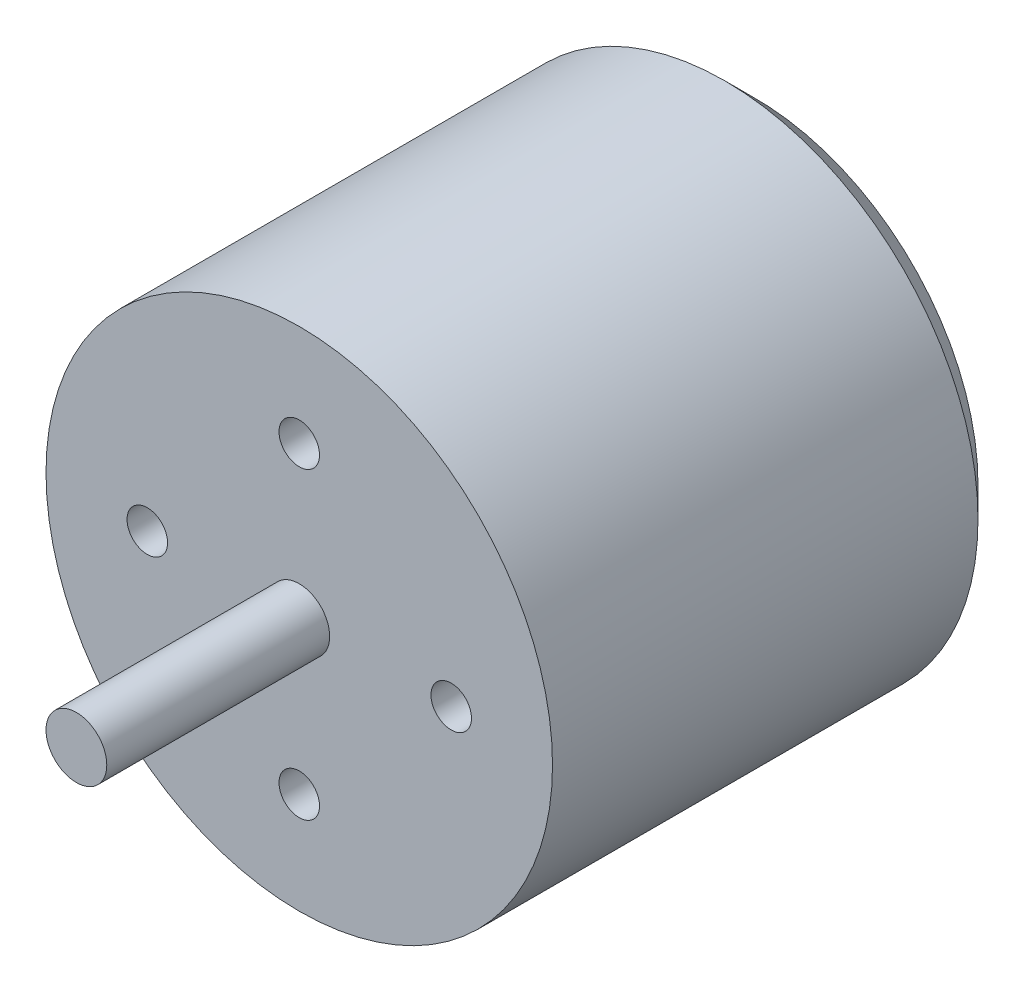
SolidWorks part; units mm, degrees
ref_plane "Front Plane" through (0, 0, 0) normal (0, 0, 1) x (1, 0, 0)
ref_plane "Top Plane" through (0, 0, 0) normal (0, 1, 0) x (1, 0, 0)
ref_plane "Right Plane" through (0, 0, 0) normal (1, 0, 0) x (0, 0, -1)
sketch "Sketch1" plane through (0, 0, 0) normal (0, 0, 1) x (1, 0, 0)
  circle A0 centre (0, 0) radius 25
  dimension "D1" = 50
extrude "Boss-Extrude1" add sketch "Sketch1" along normal blind 45 contours A0
sketch "Sketch2" plane through (0, 0, 45) normal (0, 0, 1) x (1, 0, 0)
  line L0 (-25, 0) -> (25, 0) construction
  line L1 (0, 25) -> (0, -25) construction
  circle A0 centre (0, 0) radius 25 construction
  circle A1 centre (0, 15) radius 2
  circle A2 centre (0, -15) radius 2
  circle A3 centre (-15, 0) radius 2
  circle A4 centre (15, 0) radius 2
  dimension "D1" = 4
  dimension "D2" = 30
  dimension "D3" = 4
  dimension "D4" = 30
extrude "Cut-Extrude1" cut sketch "Sketch2" against normal blind 10
sketch "Sketch3" plane through (0, 0, 45) normal (0, 0, 1) x (1, 0, 0)
  circle A0 centre (0, 0) radius 3
  dimension "D1" = 6
extrude "Boss-Extrude2" add sketch "Sketch3" along normal blind 22
sketch "Sketch4" plane through (0, 0, 0) normal (0, 0, -1) x (-1, 0, 0)
  line L0 (-25, 0) -> (25, 0) construction
  line L1 (0, 25) -> (0, -25) construction
  circle A0 centre (0, 0) radius 25 construction
  circle A1 centre (0, 10) radius 1.5
  circle A2 centre (0, -10) radius 1.5
  circle A3 centre (-10, 0) radius 1.5
  circle A4 centre (10, 0) radius 1.5
  dimension "D1" = 3
  dimension "D2" = 20
  dimension "D3" = 3
  dimension "D4" = 20
extrude "Cut-Extrude2" cut sketch "Sketch4" against normal blind 10
sketch "Sketch5" plane through (0, 0, 0) normal (0, 0, -1) x (-1, 0, 0)
  circle A0 centre (0, 0) radius 3
  dimension "D1" = 6
extrude "Boss-Extrude3" add sketch "Sketch5" along normal blind 2
ref_plane "Plane1" through (6.0858, -6.0858, 0) normal (0.7071, -0.7071, 0) x (-0.7071, -0.7071, 0)
chamfer "Chamfer1" distance 3 distance2 3 1 edges at (25, 0, 0)
